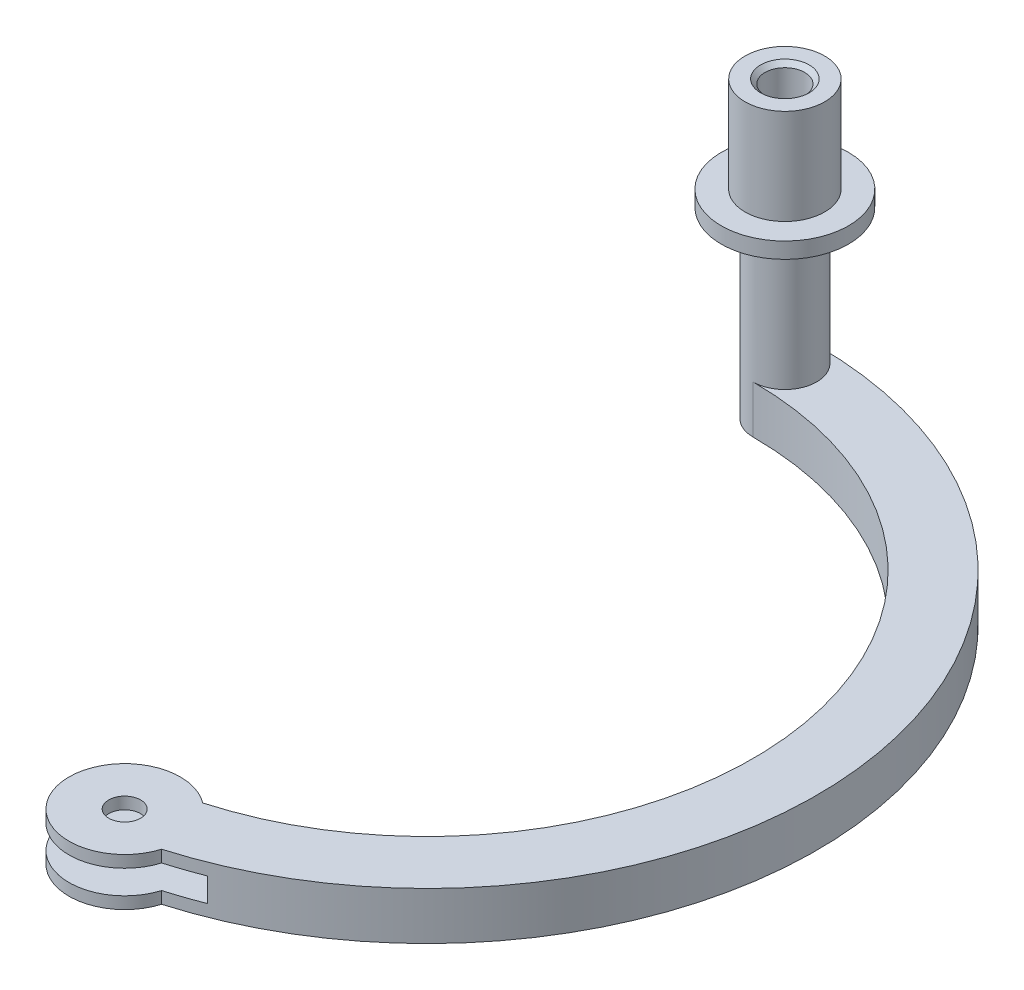
SolidWorks part; units mm, degrees
ref_plane "Front Plane" through (0, 0, 0) normal (0, 0, 1) x (1, 0, 0)
ref_plane "Top Plane" through (0, 0, 0) normal (0, 1, 0) x (1, 0, 0)
ref_plane "Right Plane" through (0, 0, 0) normal (1, 0, 0) x (0, 0, -1)
sketch "Sketch1" plane through (0, 0, 0) normal (0, 1, 0) x (1, 0, 0)
  circle A0 centre (0, 0) radius 2.5
  dimension "D1" = 5
extrude "Boss-Extrude1" add sketch "Sketch1" along normal blind 6
sketch "Sketch2" plane through (0, 0, 0) normal (0, -1, 0) x (1, 0, 0)
  circle A0 centre (0, 0) radius 4
  dimension "D1" = 8
extrude "Boss-Extrude2" add sketch "Sketch2" along normal blind 1
ref_plane "Plane1" through (0, -11, 0) normal (0, -1, 0) x (-1, 0, 0)
sketch "Sketch6" plane through (0, -11, 0) normal (0, -1, 0) x (-1, 0, 0)
  line L10 (0, 0) -> (0, -16.7806) construction
  arc A1 (-5.6195, -42.2147) -> (-6.8469, -46.0238) centre (-3.5, -45) cw
  arc A2 (0, 2) -> (0, -2) centre (0, 0) cw
  arc A3 (-6.8469, -46.0238) -> (0, 2) centre (0, -22.5) cw
  arc A4 (0, -2) -> (-5.6195, -42.2147) centre (0, -22.5) ccw
  dimension "D1" = 3.5
  dimension "D2" = 2
  dimension "D4" = 45
  dimension "D3" = 22.5
extrude "Boss-Extrude3" add sketch "Sketch6" along normal mid plane 3 separate body
sketch "Sketch7" plane through (0, -1, 0) normal (0, -1, 0) x (1, 0, 0)
  circle A3 centre (0, 0) radius 2
  arc A4 (0, 2) -> (0, -2) centre (0, 0) ccw construction
extrude "Boss-Extrude4" add sketch "Sketch7" along normal up to surface (8.5 mm away) contours A3 up to face at (10.6815, -9.5, 21.1946)
ref_plane "Plane2" through (0, -11, 0) normal (0, 1, 0) x (1, 0, 0)
sketch "Sketch8" plane through (0, -11, 0) normal (0, 1, 0) x (1, 0, 0)
  circle A0 centre (3.5, -45) radius 5.5
  arc A1 (5.6195, -42.2147) -> (6.8469, -46.0238) centre (3.5, -45) ccw construction
  dimension "D1" = 2
extrude "Cut-Extrude1" cut sketch "Sketch8" against normal mid plane 1.5
sketch "Sketch9" plane through (0, -9.5, 0) normal (0, 1, 0) x (1, 0, 0)
  circle A0 centre (3.5, -45) radius 1
  arc A1 (5.6195, -42.2147) -> (6.8469, -46.0238) centre (3.5, -45) ccw construction
  dimension "D1" = 2
extrude "Cut-Extrude2" cut sketch "Sketch9" against normal through all
sketch "Sketch10" plane through (0, 6, 0) normal (0, 1, 0) x (1, 0, 0)
  circle A0 centre (0, 0) radius 2.5 construction
  point P0 (0, 0)
hole_wizard "M3 Tapped Hole2" positions "3DSketch4" profile "Sketch12" tap size "M3" standard "ISO"
sketch3d "3DSketch4"
  point P0 (0, 6, 0)
sketch "Sketch12" plane through (0, 6, 0) normal (1, 0, 0) x (0, 0, 1)
  line L0 (0, 0) -> (0, 8.2511)
  line L1 (0, 8.2511) -> (1.25, 7.5)
  line L2 (1.25, 7.5) -> (1.25, 0.275)
  line L3 (1.25, 0.275) -> (1.525, 0)
  line L5 (1.525, 0) -> (0, 0)
  line L6 (-1.25, 0.275) -> (-1.525, 0) construction
  line L10 (0, 8.2511) -> (-1.25, 7.5) construction
  line L11 (0, -6.35) -> (0, 107.95) construction
  dimension "Tap Drill Dia." = 2.5
  dimension "Tap Drill Depth" = 7.5
  dimension "Near C'Sink Dia." = 3.05
  dimension "Near C'Sink Angle" = 90
  dimension "Drill Angle" = 118
cosmetic thread "Hole Thread2" parameters "D1"=6, "D2"=3
cosmetic thread "Cosmetic Thread1" parameters "D1"=6, "D2"=3
